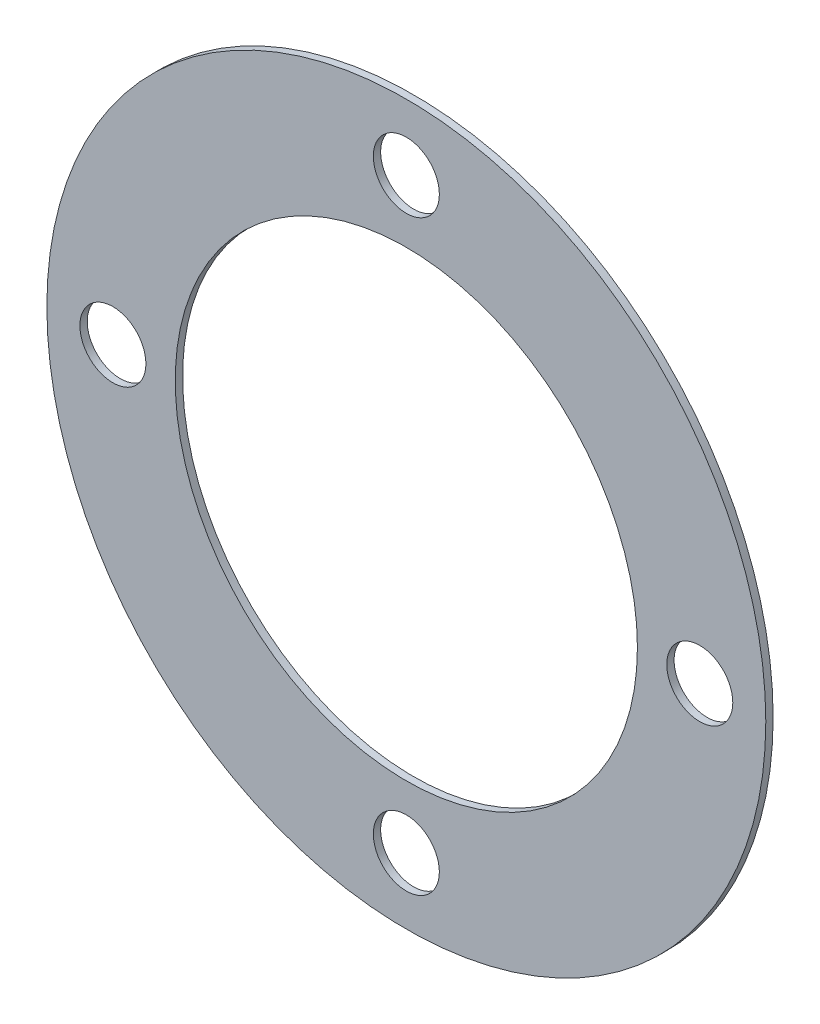
SolidWorks part; units mm, degrees
ref_plane "前视基准面" through (0, 0, 0) normal (0, 0, 1) x (1, 0, 0)
ref_plane "上视基准面" through (0, 0, 0) normal (0, 1, 0) x (1, 0, 0)
ref_plane "右视基准面" through (0, 0, 0) normal (1, 0, 0) x (0, 0, -1)
sketch "草图1" plane through (0, 0, 0) normal (0, 0, 1) x (1, 0, 0)
  circle A0 centre (0, 0) radius 49
  circle A1 centre (0, 0) radius 31.5
extrude "凸台-拉伸1" add sketch "草图1" along normal blind 1
sketch "草图2" plane through (0, 0, 1) normal (0, 0, 1) x (1, 0, 0)
  circle A0 centre (0, 40) radius 4.5
  circle A1 centre (40, 0) radius 4.5
  circle A2 centre (0, -40) radius 4.5
  circle A3 centre (-40, 0) radius 4.5
extrude "切除-拉伸1" cut sketch "草图2" against normal blind 1
